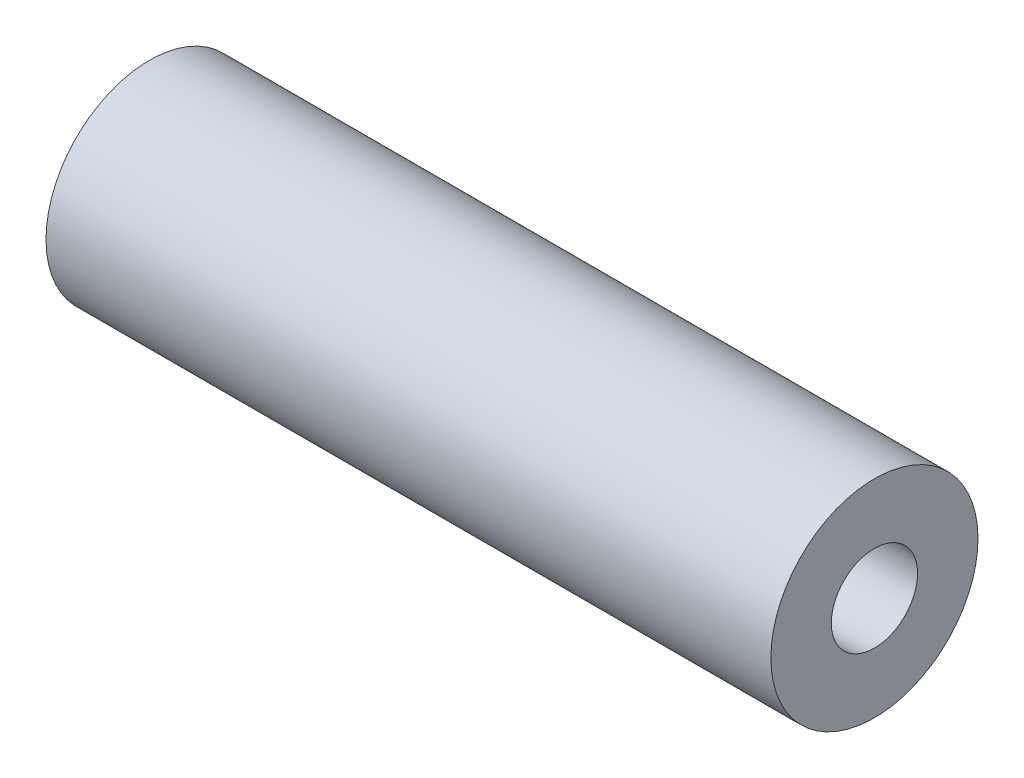
SolidWorks part; units mm, degrees
material "Rubber"
ref_plane "Front Plane" through (0, 0, 0) normal (0, 0, 1) x (1, 0, 0)
ref_plane "Top Plane" through (0, 0, 0) normal (0, 1, 0) x (1, 0, 0)
ref_plane "Right Plane" through (0, 0, 0) normal (1, 0, 0) x (0, 0, -1)
sketch "Sketch1" plane through (0, 0, 0) normal (1, 0, 0) x (0, 0, -1)
  circle A0 centre (0, 0) radius 3
  dimension "D1" = 6
extrude "Boss-Extrude1" add sketch "Sketch1" along normal blind 21
sketch "Sketch2" plane through (0, 0, 0) normal (-1, 0, 0) x (0, 0, 1)
  circle A0 centre (0, 0) radius 1.25
  dimension "D1" = 2.5
extrude "Cut-Extrude1" cut sketch "Sketch2" against normal blind 21
